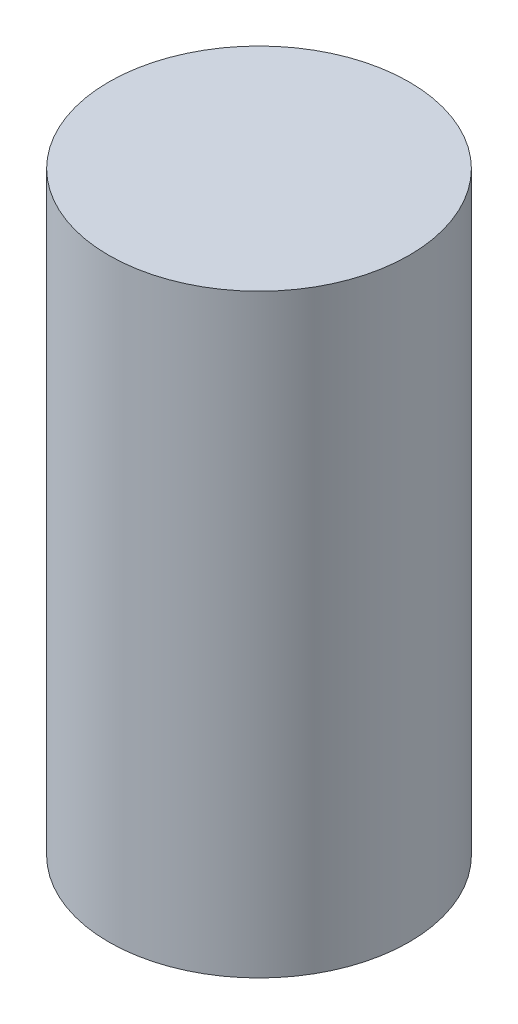
SolidWorks part; units mm, degrees
ref_plane "Front Plane" through (0, 0, 0) normal (0, 0, 1) x (1, 0, 0)
ref_plane "Top Plane" through (0, 0, 0) normal (0, 1, 0) x (1, 0, 0)
ref_plane "Right Plane" through (0, 0, 0) normal (1, 0, 0) x (0, 0, -1)
sketch "Sketch2" plane through (0, 0, 0) normal (0, 1, 0) x (1, 0, 0)
  circle A0 centre (0, 0) radius 5
  circle A1 centre (0, 0) radius 2.75
  dimension "D1" = 5.5
  dimension "D2" = 10
extrude "Boss-Extrude1" add sketch "Sketch2" along normal blind 3.8
ref_plane "Plane1" through (0, 3.8, 0) normal (0, 1, 0) x (1, 0, 0)
sketch "Sketch5" plane through (0, 3.8, 0) normal (0, 1, 0) x (1, 0, 0)
  circle A0 centre (0, 0) radius 5
  dimension "D1" = 10
extrude "Boss-Extrude2" add sketch "Sketch5" along normal blind 16
